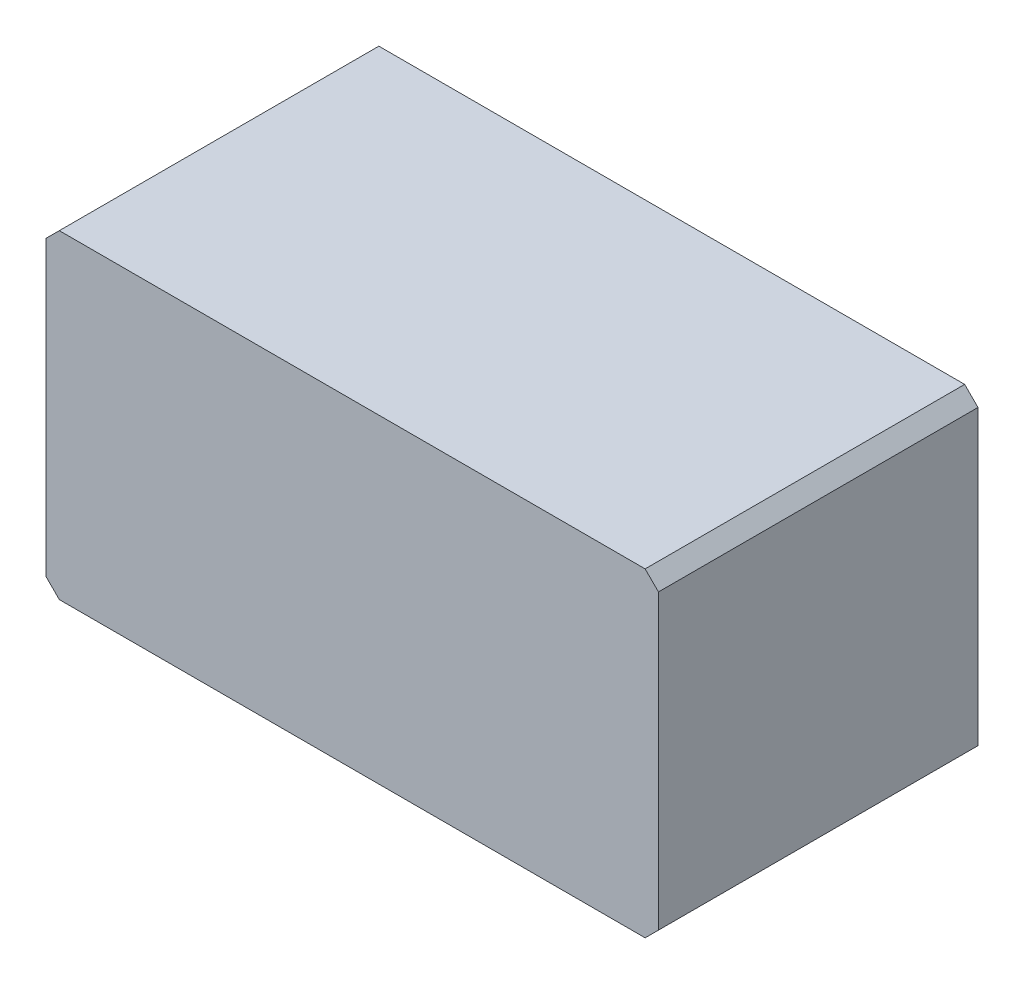
SolidWorks part; units mm, degrees
ref_plane "前视基准面" through (0, 0, 0) normal (0, 0, 1) x (1, 0, 0)
ref_plane "上视基准面" through (0, 0, 0) normal (0, 1, 0) x (1, 0, 0)
ref_plane "右视基准面" through (0, 0, 0) normal (1, 0, 0) x (0, 0, -1)
sketch "草图1" plane through (0, 0, 0) normal (0, 0, 1) x (1, 0, 0)
  line L0 (-0.575, 0.275) -> (-0.55, 0.3)
  line L1 (-0.55, 0.3) -> (0.55, 0.3)
  line L2 (0.55, 0.3) -> (0.575, 0.275)
  line L3 (0.575, 0.275) -> (0.575, -0.275)
  line L4 (0.575, -0.275) -> (0.55, -0.3)
  line L5 (0.55, -0.3) -> (-0.55, -0.3)
  line L6 (-0.55, -0.3) -> (-0.575, -0.275)
  line L7 (-0.575, -0.275) -> (-0.575, 0.275)
extrude "Component_Outline" add sketch "草图1" along normal blind 0.6 separate body
sketch3d "3D草图1"
  line L0 (0, 0, 0) -> (1, 0, 0)
  line L1 (0, 0, 0) -> (0, 1, 0)
  line L2 (0, 0, 0) -> (0, 0, 1)
  point P0 (0, 0, 0)
